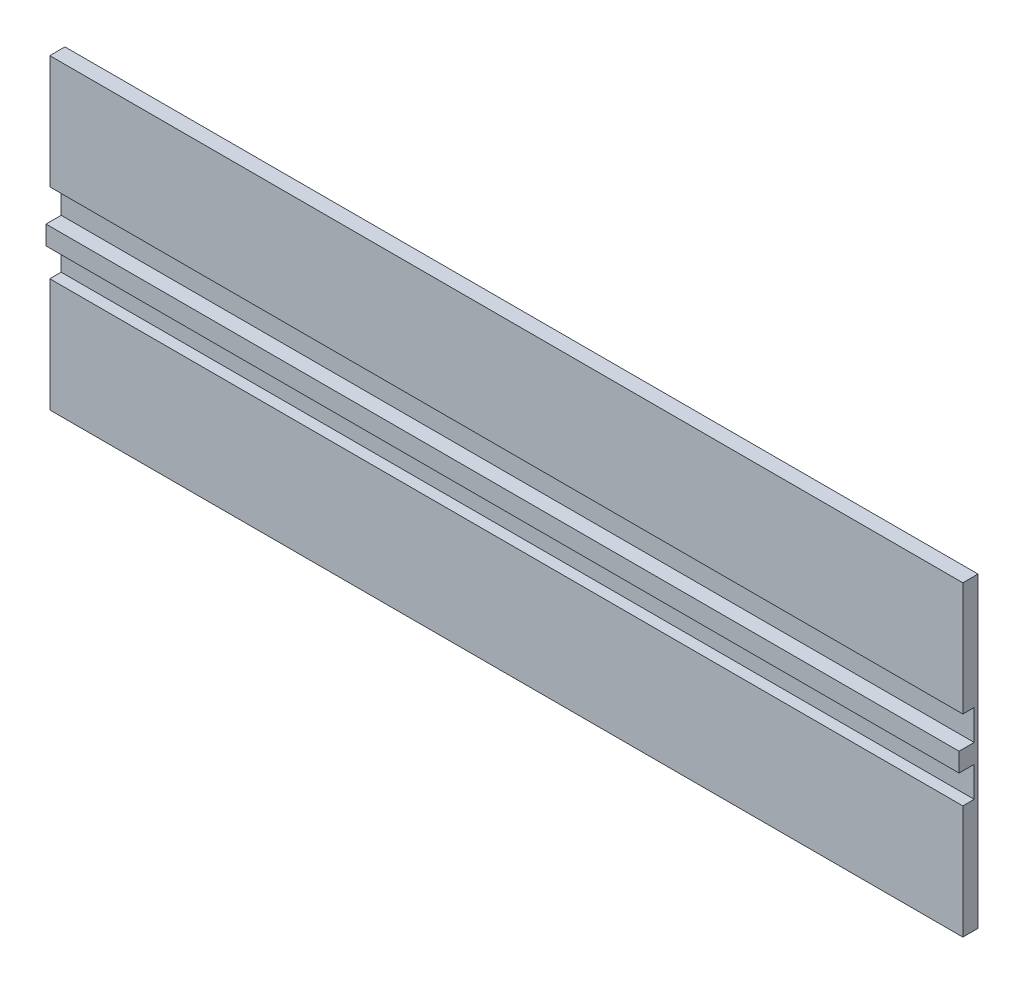
SolidWorks part; units mm, degrees
ref_plane "Ebene vorne" through (0, 0, 0) normal (0, 0, 1) x (1, 0, 0)
ref_plane "Ebene oben" through (0, 0, 0) normal (0, 1, 0) x (1, 0, 0)
ref_plane "Ebene rechts" through (0, 0, 0) normal (1, 0, 0) x (0, 0, -1)
sketch "Skizze1" plane through (0, 0, 0) normal (0, 0, 1) x (1, 0, 0)
  line L1 (0, 0) -> (12050, 0)
  line L2 (0, 0) -> (0, 4050)
  line L3 (0, 4050) -> (12050, 4050)
  line L4 (12050, 0) -> (12050, 4050)
  dimension "D1" = 12050
  dimension "D2" = 4050
extrude "Aufsatz-Linear austragen1" add sketch "Skizze1" along normal blind 200
sketch "Skizze2" plane through (12050, 0, 0) normal (1, 0, 0) x (0, 0, -1)
  line L0 (-200, 0) -> (-200, 4050) construction
  line L1 (-200, 2550) -> (-50, 2550)
  line L2 (-200, 2550) -> (-200, 1500)
  line L3 (-200, 1500) -> (-50, 1500)
  line L4 (-50, 2550) -> (-50, 1500)
  line L5 (-200, 4050) -> (0, 4050) construction
  dimension "D1" = 1500
  dimension "D2" = 1500
  dimension "D3" = 150
extrude "Schnitt-Linear austragen1" cut sketch "Skizze2" against normal through all
sketch "Skizze3" plane through (12050, 0, 0) normal (1, 0, 0) x (0, 0, -1)
  line L0 (-50, 1500) -> (-50, 2550) construction
  line L1 (-50, 2550) -> (-200, 2550) construction
  line L2 (-50, 2150) -> (-250, 2150)
  line L3 (-50, 2150) -> (-50, 1900)
  line L4 (-50, 1900) -> (-250, 1900)
  line L5 (-250, 2150) -> (-250, 1900)
  line L6 (-200, 1500) -> (-50, 1500) construction
  dimension "D1" = 200
  dimension "D2" = 400
  dimension "D3" = 400
extrude "Aufsatz-Linear austragen2" add sketch "Skizze3" against normal blind 12050
